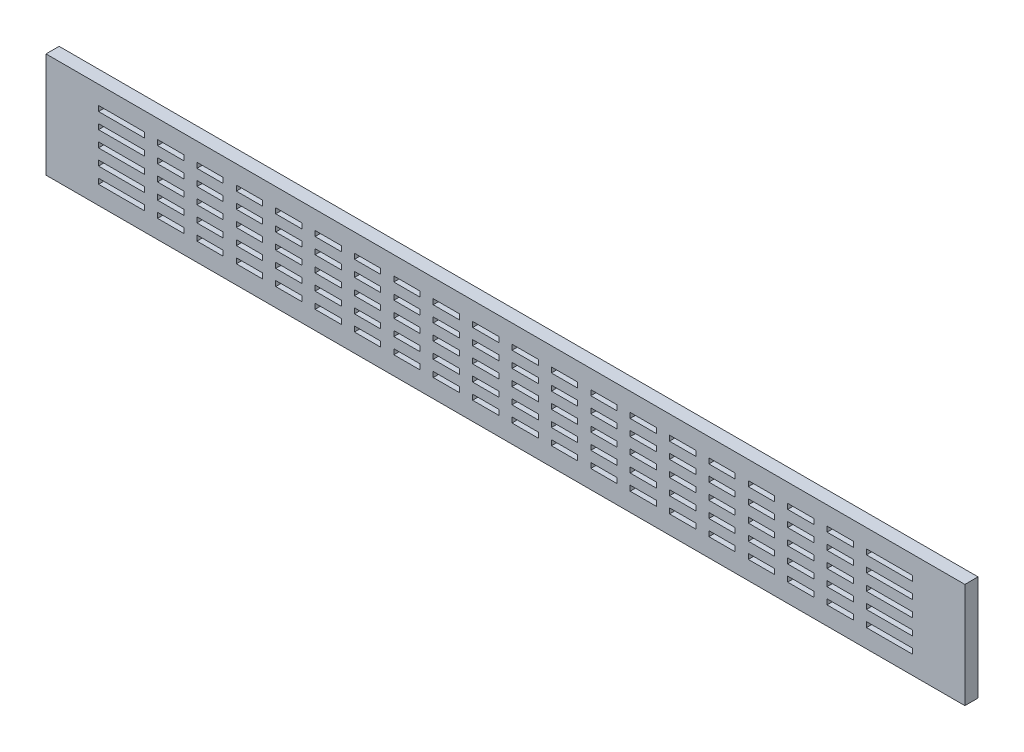
SolidWorks part; units mm, degrees
ref_plane "前视基准面" through (0, 0, 0) normal (0, 0, 1) x (1, 0, 0)
ref_plane "上视基准面" through (0, 0, 0) normal (0, 1, 0) x (1, 0, 0)
ref_plane "右视基准面" through (0, 0, 0) normal (1, 0, 0) x (0, 0, -1)
sketch "草图1" plane through (0, 0, 0) normal (0, 0, 1) x (1, 0, 0)
  line L1 (-175, 20) -> (175, 20)
  line L2 (-175, 20) -> (-175, -20)
  line L3 (-175, -20) -> (175, -20)
  line L4 (175, 20) -> (175, -20)
  line L5 (0, -20) -> (0, 20) construction
  line L6 (-175, 0) -> (175, 0) construction
  point P0 (0, 0)
  dimension "D1" = 350
  dimension "D2" = 40
extrude "凸台-拉伸1" add sketch "草图1" along normal blind 5
sketch "草图2" plane through (0, 0, 5) normal (0, 0, 1) x (1, 0, 0)
  line L0 (175, -20) -> (175, 20) construction
  line L1 (-155, 1) -> (155, 1)
  line L2 (-155, 1) -> (-155, -1)
  line L3 (-155, -1) -> (155, -1)
  line L4 (155, 1) -> (155, -1)
  line L5 (0, -1) -> (0, 1) construction
  line L6 (-155, 0) -> (155, 0) construction
  line L7 (-155, -5) -> (-155, -7)
  line L8 (-155, -5) -> (155, -5)
  line L9 (155, -5) -> (155, -7)
  line L10 (-155, -7) -> (155, -7)
  line L11 (-155, -11) -> (-155, -13)
  line L12 (-155, -11) -> (155, -11)
  line L13 (155, -11) -> (155, -13)
  line L14 (-155, -13) -> (155, -13)
  line L16 (-155, 11) -> (155, 11)
  line L17 (155, 11) -> (155, 13)
  line L18 (-155, 13) -> (155, 13)
  line L19 (-155, 11) -> (-155, 13)
  line L20 (-155, 5) -> (155, 5)
  line L21 (155, 5) -> (155, 7)
  line L22 (-155, 7) -> (155, 7)
  line L23 (-155, 5) -> (-155, 7)
  point P0 (0, 0)
  dimension "D1" = 2
  dimension "D2" = 20
  dimension "D3" = 3
extrude "切除-拉伸1" cut sketch "草图2" against normal through all
sketch "草图3" plane through (0, 0, 5) normal (0, 0, 1) x (1, 0, 0)
  line L0 (-155, -13) -> (155, -13) construction
  line L1 (-2.5, 13) -> (2.5, 13)
  line L2 (-2.5, 13) -> (-2.5, -13)
  line L3 (-2.5, -13) -> (2.5, -13)
  line L4 (2.5, 13) -> (2.5, -13)
  line L5 (0, -13) -> (0, 13) construction
  line L6 (-2.5, 0) -> (2.5, 0) construction
  line L7 (12.5, 13) -> (12.5, -13)
  line L8 (12.5, 13) -> (17.5, 13)
  line L9 (17.5, 13) -> (17.5, -13)
  line L10 (12.5, -13) -> (17.5, -13)
  line L11 (27.5, 13) -> (27.5, -13)
  line L12 (27.5, 13) -> (32.5, 13)
  line L13 (32.5, 13) -> (32.5, -13)
  line L14 (27.5, -13) -> (32.5, -13)
  line L15 (42.5, 13) -> (42.5, -13)
  line L16 (42.5, 13) -> (47.5, 13)
  line L17 (47.5, 13) -> (47.5, -13)
  line L18 (42.5, -13) -> (47.5, -13)
  line L19 (57.5, 13) -> (57.5, -13)
  line L20 (57.5, 13) -> (62.5, 13)
  line L21 (62.5, 13) -> (62.5, -13)
  line L22 (57.5, -13) -> (62.5, -13)
  line L23 (72.5, 13) -> (72.5, -13)
  line L24 (72.5, 13) -> (77.5, 13)
  line L25 (77.5, 13) -> (77.5, -13)
  line L26 (72.5, -13) -> (77.5, -13)
  line L27 (87.5, 13) -> (87.5, -13)
  line L28 (87.5, 13) -> (92.5, 13)
  line L29 (92.5, 13) -> (92.5, -13)
  line L30 (87.5, -13) -> (92.5, -13)
  line L31 (102.5, 13) -> (102.5, -13)
  line L32 (102.5, 13) -> (107.5, 13)
  line L33 (107.5, 13) -> (107.5, -13)
  line L34 (102.5, -13) -> (107.5, -13)
  line L35 (117.5, 13) -> (117.5, -13)
  line L36 (117.5, 13) -> (122.5, 13)
  line L37 (122.5, 13) -> (122.5, -13)
  line L38 (117.5, -13) -> (122.5, -13)
  line L39 (132.5, 13) -> (132.5, -13)
  line L40 (132.5, 13) -> (137.5, 13)
  line L41 (137.5, 13) -> (137.5, -13)
  line L42 (132.5, -13) -> (137.5, -13)
  line L43 (-132.5, -13) -> (-137.5, -13)
  line L44 (-137.5, 13) -> (-137.5, -13)
  line L45 (-132.5, 13) -> (-137.5, 13)
  line L46 (-132.5, 13) -> (-132.5, -13)
  line L47 (-117.5, -13) -> (-122.5, -13)
  line L48 (-122.5, 13) -> (-122.5, -13)
  line L49 (-117.5, 13) -> (-122.5, 13)
  line L50 (-117.5, 13) -> (-117.5, -13)
  line L51 (-102.5, -13) -> (-107.5, -13)
  line L52 (-107.5, 13) -> (-107.5, -13)
  line L53 (-102.5, 13) -> (-107.5, 13)
  line L54 (-102.5, 13) -> (-102.5, -13)
  line L55 (-87.5, -13) -> (-92.5, -13)
  line L56 (-92.5, 13) -> (-92.5, -13)
  line L57 (-87.5, 13) -> (-92.5, 13)
  line L58 (-87.5, 13) -> (-87.5, -13)
  line L59 (-72.5, -13) -> (-77.5, -13)
  line L60 (-77.5, 13) -> (-77.5, -13)
  line L61 (-72.5, 13) -> (-77.5, 13)
  line L62 (-72.5, 13) -> (-72.5, -13)
  line L63 (-57.5, -13) -> (-62.5, -13)
  line L64 (-62.5, 13) -> (-62.5, -13)
  line L65 (-57.5, 13) -> (-62.5, 13)
  line L66 (-57.5, 13) -> (-57.5, -13)
  line L67 (-42.5, -13) -> (-47.5, -13)
  line L68 (-47.5, 13) -> (-47.5, -13)
  line L69 (-42.5, 13) -> (-47.5, 13)
  line L70 (-42.5, 13) -> (-42.5, -13)
  line L71 (-27.5, -13) -> (-32.5, -13)
  line L72 (-32.5, 13) -> (-32.5, -13)
  line L73 (-27.5, 13) -> (-32.5, 13)
  line L74 (-27.5, 13) -> (-27.5, -13)
  line L75 (-12.5, -13) -> (-17.5, -13)
  line L76 (-17.5, 13) -> (-17.5, -13)
  line L77 (-12.5, 13) -> (-17.5, 13)
  line L78 (-12.5, 13) -> (-12.5, -13)
  point P0 (0, 0)
  dimension "D1" = 5
  dimension "D2" = 10
extrude "凸台-拉伸2" add sketch "草图3" against normal up to surface (5 mm away) up to face at (0, 6, 0)
